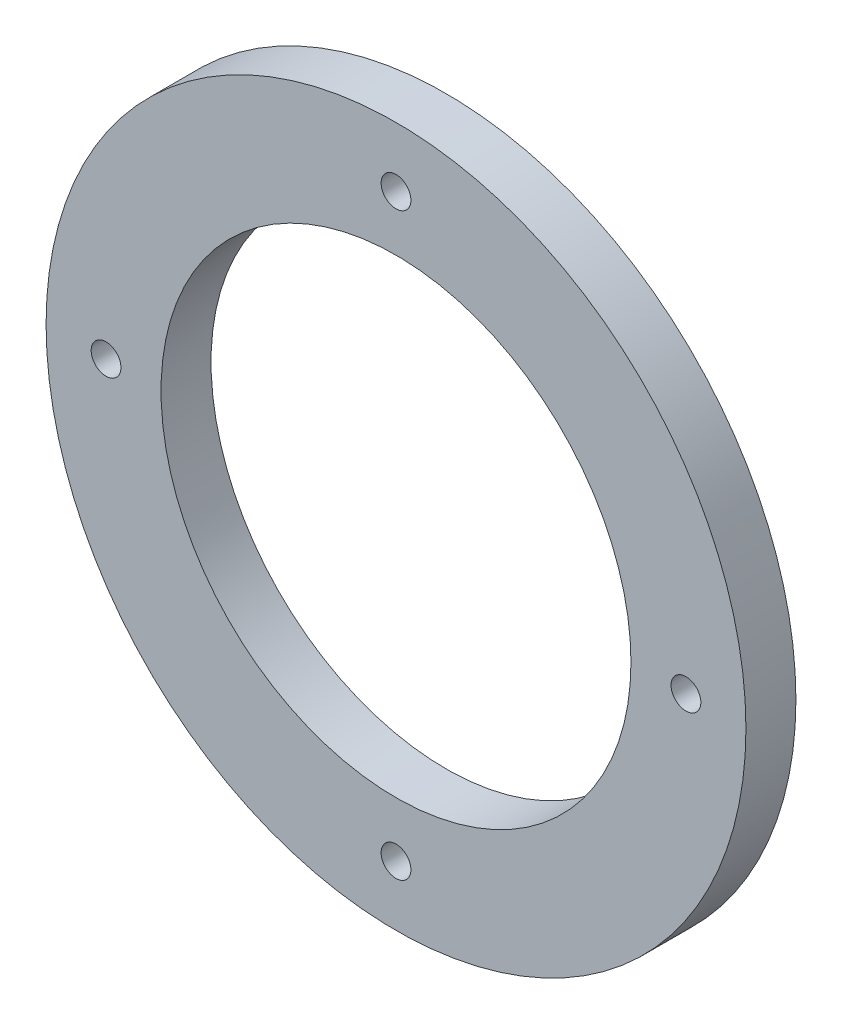
SolidWorks part; units mm, degrees
ref_plane "Front Plane" through (0, 0, 0) normal (0, 0, 1) x (1, 0, 0)
ref_plane "Top Plane" through (0, 0, 0) normal (0, 1, 0) x (1, 0, 0)
ref_plane "Right Plane" through (0, 0, 0) normal (1, 0, 0) x (0, 0, -1)
sketch "Sketch1" plane through (0, 0, 0) normal (0, 0, 1) x (1, 0, 0)
  circle A0 centre (0, 0) radius 35
  circle A1 centre (0, 0) radius 23.5
  circle A3 centre (29, 0) radius 1.49
  circle A4 centre (0, 29) radius 1.49
  circle A5 centre (-29, 0) radius 1.49
  circle A6 centre (0, -29) radius 1.49
  dimension "D1" = 70
  dimension "D2" = 47
  dimension "D3" = 2.98
  dimension "D4" = 2.98
  dimension "D5" = 2.98
  dimension "D6" = 2.98
  dimension "D7" = 29
  dimension "D8" = 29
  dimension "D9" = 29
  dimension "D10" = 29
extrude "Boss-Extrude1" add sketch "Sketch1" along normal blind 5
